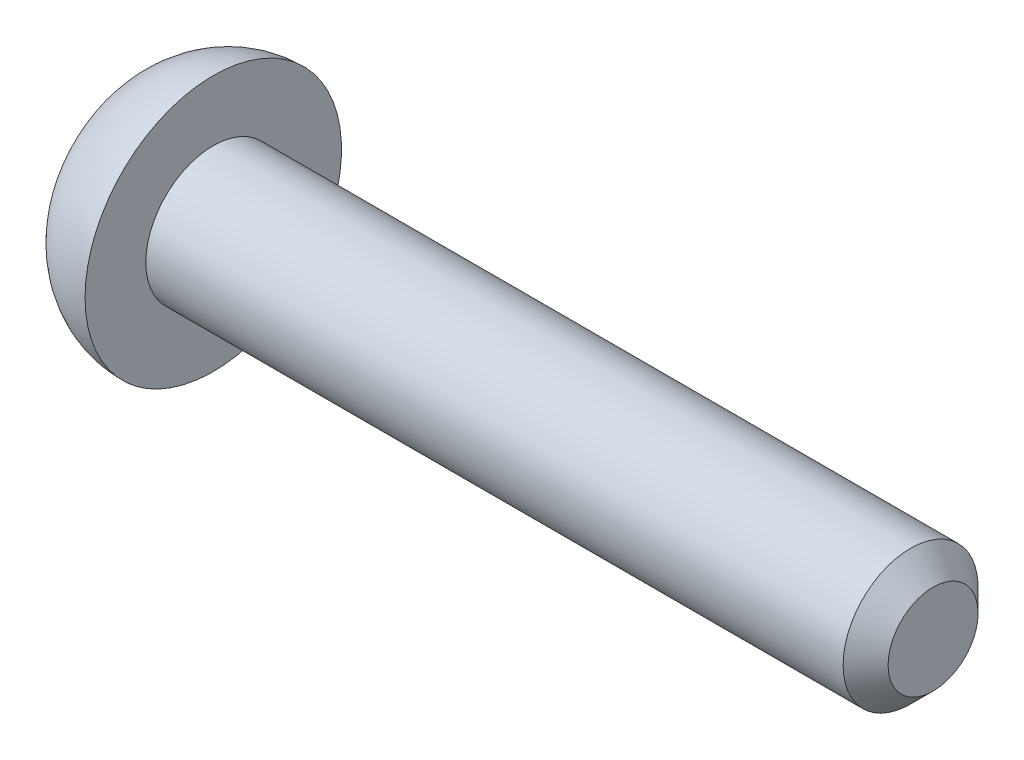
SolidWorks part; units mm, degrees
ref_plane "Front Plane" through (0, 0, 0) normal (0, 0, 1) x (1, 0, 0)
ref_plane "Top Plane" through (0, 0, 0) normal (0, 1, 0) x (1, 0, 0)
ref_plane "Right Plane" through (0, 0, 0) normal (1, 0, 0) x (0, 0, -1)
sketch "Sketch2" plane through (0, 0, 0) normal (0, 1, 0) x (1, 0, 0)
  line L0 (0, 0) -> (0, 1.5)
  line L1 (0, -3.135) -> (0, 3.135) construction
  line L2 (0, 1.5) -> (-16, 1.5)
  line L3 (-16, 1.5) -> (-16, 0) construction
  line L4 (-3.135, 0) -> (3.135, 0) construction
  line L5 (-17.65, 2.049) -> (-17.65, 0)
  line L6 (-17.65, 0) -> (0, 0)
  line L7 (-16, 2.85) -> (-16, 1.5)
  arc A0 (-17.65, 2.049) -> (-16, 2.85) centre (-16, 0.75) cw
  dimension "D2" = 16
  dimension "D3" = 2.85
  dimension "D1" = 1.65
  dimension "D4" = 1.5
revolve "Revolve1" add sketch "Sketch2" angle 360 about L6
chamfer "Chamfer1" distance 0.5 angle 45 1 edges at (0, 0, 1.5)
sketch "Sketch4" plane through (-17.65, 0, 0) normal (-1, 0, 0) x (0, 0, 1)
  line L1 (0.8389, 1.453) -> (-0.8389, 1.453) construction
  line L2 (-0.8389, 1.453) -> (-1.6778, 0) construction
  line L3 (-1.6778, 0) -> (-0.8389, -1.453) construction
  line L4 (-0.8389, -1.453) -> (0.8389, -1.453) construction
  line L5 (0.8389, -1.453) -> (1.6778, 0) construction
  line L6 (1.6778, 0) -> (0.8389, 1.453) construction
  circle A0 centre (0, 0) radius 1.453 construction
  arc A1 (-1.342, 0.0907) -> (-0.7496, 1.1169) centre (-1.7745, 1.0245) ccw
  arc A2 (-0.5924, 1.2076) -> (0.5924, 1.2076) centre (0, 2.049) ccw
  arc A3 (0.7496, 1.1169) -> (1.342, 0.0907) centre (1.7745, 1.0245) ccw
  arc A4 (1.342, -0.0907) -> (0.7496, -1.1169) centre (1.7745, -1.0245) ccw
  arc A5 (-0.5924, -1.2076) -> (0.5924, -1.2076) centre (0, -2.049) cw
  arc A6 (-0.7496, -1.1169) -> (-1.342, -0.0907) centre (-1.7745, -1.0245) ccw
  circle A7 centre (0, 0) radius 2.049 construction
  arc A8 (0.7496, 1.1169) -> (0.5924, 1.2076) centre (0.65, 1.1258) ccw
  arc A9 (1.342, -0.0907) -> (1.342, 0.0907) centre (1.3, 0) ccw
  arc A10 (0.7496, -1.1169) -> (0.5924, -1.2076) centre (0.65, -1.1258) cw
  arc A11 (-0.7496, -1.1169) -> (-0.5924, -1.2076) centre (-0.65, -1.1258) ccw
  arc A12 (-1.342, 0.0907) -> (-1.342, -0.0907) centre (-1.3, 0) ccw
  arc A13 (-0.7496, 1.1169) -> (-0.5924, 1.2076) centre (-0.65, 1.1258) cw
  circle A14 centre (0, 0) radius 2.049 construction
  point P40 (2.049, 0)
  dimension "D1" = 0.1
  dimension "D2" = 2.6
extrude "Cut-Extrude1" cut sketch "Sketch4" against normal blind 1
equation "\"d1\"= 3"
equation "\"l\"= 16"
equation "\"d2\"= 5.7"
equation "\"t\"= 1"
equation "\"k\"=1.65"
equation "\"A\"=2.8"
equation "\"D3@Sketch2\"=\"d2\" / 2"
equation "\"D1@Sketch2\"= \"k\""
equation "\"D4@Sketch2\"=\"d1\" / 2"
equation "\"D2@Sketch4\"= \"A\" - 2 * \"D1@Sketch4\""
equation "\"D1@Cut-Extrude1\"= \"t\""
equation "\"D2@Sketch2\"=\"l\""
